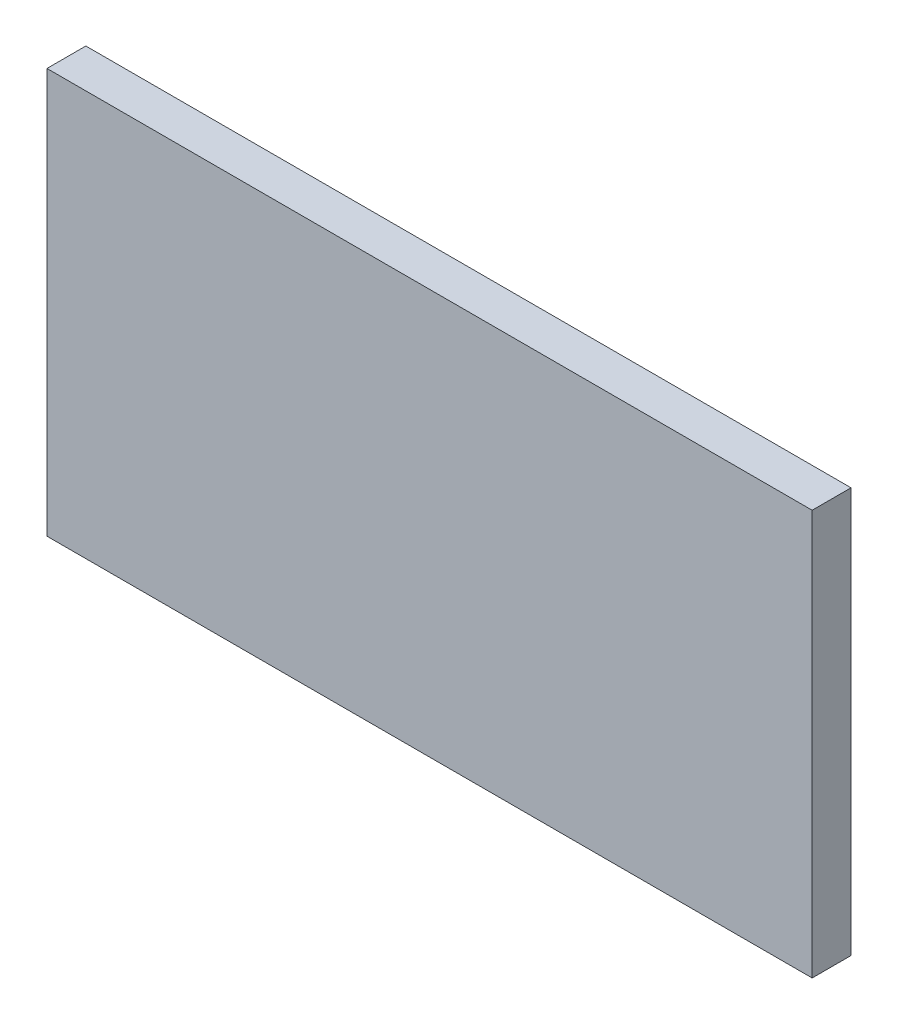
SolidWorks part; units mm, degrees
ref_plane "Plan de face" through (0, 0, 0) normal (0, 0, 1) x (1, 0, 0)
ref_plane "Plan de dessus" through (0, 0, 0) normal (0, 1, 0) x (1, 0, 0)
ref_plane "Plan de droite" through (0, 0, 0) normal (1, 0, 0) x (0, 0, -1)
sketch "Esquisse1" plane through (0, 0, 0) normal (0, 0, 1) x (1, 0, 0)
  line L1 (0, 0) -> (374, 0)
  line L2 (0, 0) -> (0, 198)
  line L3 (0, 198) -> (374, 198)
  line L4 (374, 0) -> (374, 198)
  dimension "D1" = 198
  dimension "D2" = 374
extrude "Boss.-Extru.1" add sketch "Esquisse1" along normal blind 19
sketch "Esquisse2" plane through (374, 0, 0) normal (1, 0, 0) x (0, 0, -1)
  line L0 (-9.5, 198) -> (-9.5, 0) construction
  line L1 (-19, 198) -> (0, 198) construction
  line L2 (-19, 0) -> (0, 0) construction
  line L3 (-19, 0) -> (-19, 198) construction
  dimension "D1" = 9.5
